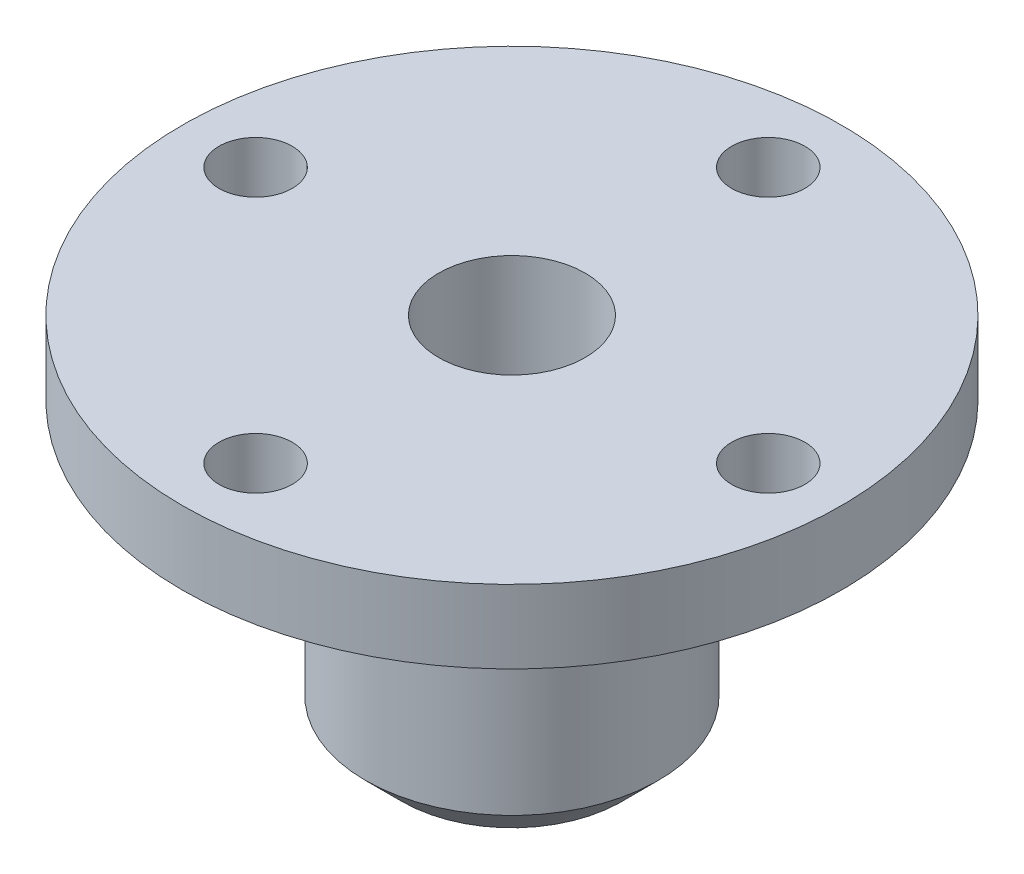
SolidWorks part; units mm, degrees
ref_plane "Přední rovina" through (0, 0, 0) normal (0, 0, 1) x (1, 0, 0)
ref_plane "Horní rovina" through (0, 0, 0) normal (0, 1, 0) x (1, 0, 0)
ref_plane "Pravá rovina" through (0, 0, 0) normal (1, 0, 0) x (0, 0, -1)
sketch "Skica1" plane through (0, 0, 0) normal (0, 1, 0) x (1, 0, 0)
  circle A0 centre (0, 0) radius 45
  dimension "D1" = 90
extrude "Přidat vysunutím1" add sketch "Skica1" along normal blind 10
sketch "Skica3" plane through (0, 10, 0) normal (0, 1, 0) x (1, 0, 0)
  circle A0 centre (0, 0) radius 35 construction
  circle A2 centre (0, 35) radius 5
  dimension "D1" = 70
  dimension "D2" = 10
extrude "Odebrat vysunutím1" cut sketch "Skica3" against normal through all
pattern_circular "Kruhové pole1" count 4 over 360 about axis through (0, 0, 0) along (0, 1, 0) of "Odebrat vysunutím1"
sketch "Skica4" plane through (0, 10, 0) normal (0, 1, 0) x (1, 0, 0)
  circle A0 centre (0, 0) radius 20
  dimension "D1" = 40
extrude "Přidat vysunutím2" add sketch "Skica4" against normal blind 50
sketch "Skica5" plane through (0, -40, 0) normal (0, -1, 0) x (1, 0, 0)
  circle A0 centre (0, 0) radius 10
  dimension "D1" = 20
extrude "Odebrat vysunutím2" cut sketch "Skica5" against normal through all
fillet "Zaoblit1" radius 5 1 edges at (0, 0, 20)
chamfer "Zkosení1" distance 5 1 edges at (0, -40, 20)
